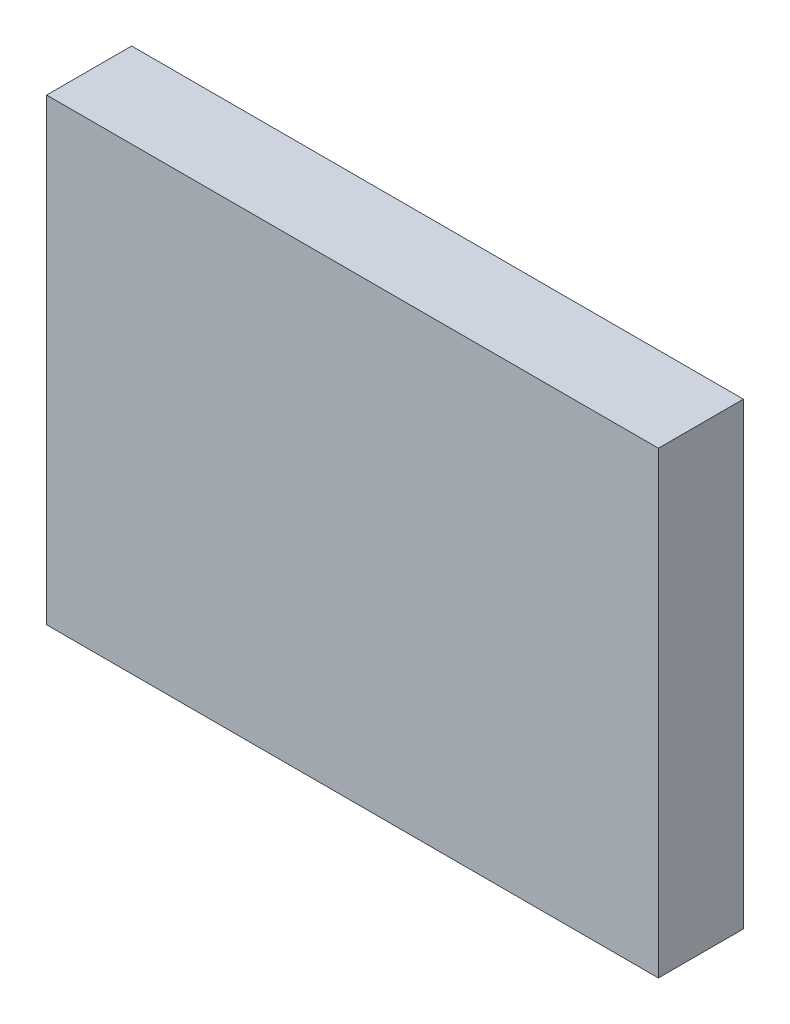
SolidWorks part; units mm, degrees
ref_plane "Спереди" through (0, 0, 0) normal (0, 0, 1) x (1, 0, 0)
ref_plane "Сверху" through (0, 0, 0) normal (0, 1, 0) x (1, 0, 0)
ref_plane "Справа" through (0, 0, 0) normal (1, 0, 0) x (0, 0, -1)
sketch "Эскиз1" plane through (0, 0, 0) normal (0, 0, 1) x (1, 0, 0)
  line L1 (-180, 135) -> (180, 135)
  line L2 (-180, 135) -> (-180, -135)
  line L3 (-180, -135) -> (180, -135)
  line L4 (180, 135) -> (180, -135)
  line L5 (-180, 135) -> (180, -135) construction
  line L6 (-180, -135) -> (180, 135) construction
  point P0 (0, 0)
extrude "Бобышка-Вытянуть1" add sketch "Эскиз1" along normal blind 50
sketch "шлифовка" plane through (0, 0, 50) normal (0, 0, 1) x (1, 0, 0)
  line L1 (-34.1581, 21.8035) -> (-171.6039, 21.8035)
  line L2 (-34.1581, 21.8035) -> (-34.1581, 9.8035)
  line L3 (-34.1581, 9.8035) -> (-171.6039, 9.8035)
  line L4 (-171.6039, 21.8035) -> (-171.6039, 9.8035)
sketch3d "Трехмерный эскиз1"
  point P0 (0, 0, 50.02)
sketch "Перлаж" plane through (0, 0, 50) normal (0, 0, 1) x (1, 0, 0)
  circle A149 centre (-138.9139, -231.1186) radius 1.47
  circle A150 centre (-137.3639, -231.1186) radius 1.47
  circle A151 centre (-135.8139, -231.1186) radius 1.47
  circle A152 centre (-134.2639, -231.1186) radius 1.47
  circle A153 centre (-132.7139, -231.1186) radius 1.47
  circle A154 centre (-131.1639, -231.1186) radius 1.47
  circle A155 centre (-129.6139, -231.1186) radius 1.47
  circle A156 centre (-128.0639, -231.1186) radius 1.47
  circle A157 centre (-126.5139, -231.1186) radius 1.47
  circle A158 centre (-124.9639, -231.1186) radius 1.47
  circle A159 centre (-137.3639, -229.5686) radius 1.47
  circle A160 centre (-135.8139, -229.5686) radius 1.47
  circle A161 centre (-134.2639, -229.5686) radius 1.47
  circle A162 centre (-132.7139, -229.5686) radius 1.47
  circle A163 centre (-131.1639, -229.5686) radius 1.47
  circle A164 centre (-129.6139, -229.5686) radius 1.47
  circle A165 centre (-128.0639, -229.5686) radius 1.47
  circle A166 centre (-126.5139, -229.5686) radius 1.47
  circle A167 centre (-124.9639, -229.5686) radius 1.47
  circle A168 centre (-137.3639, -228.0186) radius 1.47
  circle A169 centre (-135.8139, -228.0186) radius 1.47
  circle A170 centre (-134.2639, -228.0186) radius 1.47
  circle A171 centre (-132.7139, -228.0186) radius 1.47
  circle A172 centre (-131.1639, -228.0186) radius 1.47
  circle A173 centre (-129.6139, -228.0186) radius 1.47
  circle A174 centre (-128.0639, -228.0186) radius 1.47
  circle A175 centre (-126.5139, -228.0186) radius 1.47
  circle A176 centre (-124.9639, -228.0186) radius 1.47
  circle A177 centre (-137.3639, -226.4686) radius 1.47
  circle A178 centre (-135.8139, -226.4686) radius 1.47
  circle A179 centre (-134.2639, -226.4686) radius 1.47
  circle A180 centre (-132.7139, -226.4686) radius 1.47
  circle A181 centre (-131.1639, -226.4686) radius 1.47
  circle A182 centre (-129.6139, -226.4686) radius 1.47
  circle A183 centre (-128.0639, -226.4686) radius 1.47
  circle A184 centre (-126.5139, -226.4686) radius 1.47
  circle A185 centre (-124.9639, -226.4686) radius 1.47
  circle A186 centre (-137.3639, -224.9186) radius 1.47
  circle A187 centre (-135.8139, -224.9186) radius 1.47
  circle A188 centre (-134.2639, -224.9186) radius 1.47
  circle A189 centre (-132.7139, -224.9186) radius 1.47
  circle A190 centre (-131.1639, -224.9186) radius 1.47
  circle A191 centre (-129.6139, -224.9186) radius 1.47
  circle A192 centre (-128.0639, -224.9186) radius 1.47
  circle A193 centre (-126.5139, -224.9186) radius 1.47
  circle A194 centre (-124.9639, -224.9186) radius 1.47
  circle A195 centre (-137.3639, -223.3686) radius 1.47
  circle A196 centre (-135.8139, -223.3686) radius 1.47
  circle A197 centre (-134.2639, -223.3686) radius 1.47
  circle A198 centre (-132.7139, -223.3686) radius 1.47
  circle A199 centre (-131.1639, -223.3686) radius 1.47
  circle A200 centre (-129.6139, -223.3686) radius 1.47
  circle A201 centre (-128.0639, -223.3686) radius 1.47
  circle A202 centre (-126.5139, -223.3686) radius 1.47
  circle A203 centre (-124.9639, -223.3686) radius 1.47
  circle A204 centre (-137.3639, -221.8186) radius 1.47
  circle A205 centre (-135.8139, -221.8186) radius 1.47
  circle A206 centre (-134.2639, -221.8186) radius 1.47
  circle A207 centre (-132.7139, -221.8186) radius 1.47
  circle A208 centre (-131.1639, -221.8186) radius 1.47
  circle A209 centre (-129.6139, -221.8186) radius 1.47
  circle A210 centre (-128.0639, -221.8186) radius 1.47
  circle A211 centre (-126.5139, -221.8186) radius 1.47
  circle A212 centre (-124.9639, -221.8186) radius 1.47
  circle A213 centre (-137.3639, -220.2686) radius 1.47
  circle A214 centre (-135.8139, -220.2686) radius 1.47
  circle A215 centre (-134.2639, -220.2686) radius 1.47
  circle A216 centre (-132.7139, -220.2686) radius 1.47
  circle A217 centre (-131.1639, -220.2686) radius 1.47
  circle A218 centre (-129.6139, -220.2686) radius 1.47
  circle A219 centre (-128.0639, -220.2686) radius 1.47
  circle A220 centre (-126.5139, -220.2686) radius 1.47
  circle A221 centre (-124.9639, -220.2686) radius 1.47
  circle A222 centre (-137.3639, -218.7186) radius 1.47
  circle A223 centre (-135.8139, -218.7186) radius 1.47
  circle A224 centre (-134.2639, -218.7186) radius 1.47
  circle A225 centre (-132.7139, -218.7186) radius 1.47
  circle A226 centre (-131.1639, -218.7186) radius 1.47
  circle A227 centre (-129.6139, -218.7186) radius 1.47
  circle A228 centre (-128.0639, -218.7186) radius 1.47
  circle A229 centre (-126.5139, -218.7186) radius 1.47
  circle A230 centre (-124.9639, -218.7186) radius 1.47
  circle A231 centre (-137.3639, -217.1686) radius 1.47
  circle A232 centre (-135.8139, -217.1686) radius 1.47
  circle A233 centre (-134.2639, -217.1686) radius 1.47
  circle A234 centre (-132.7139, -217.1686) radius 1.47
  circle A235 centre (-131.1639, -217.1686) radius 1.47
  circle A236 centre (-129.6139, -217.1686) radius 1.47
  circle A237 centre (-128.0639, -217.1686) radius 1.47
  circle A238 centre (-126.5139, -217.1686) radius 1.47
  circle A239 centre (-124.9639, -217.1686) radius 1.47
  circle A240 centre (-138.9139, -229.5686) radius 1.47
  circle A241 centre (-138.9139, -228.0186) radius 1.47
  circle A242 centre (-138.9139, -226.4686) radius 1.47
  circle A243 centre (-138.9139, -224.9186) radius 1.47
  circle A244 centre (-138.9139, -223.3686) radius 1.47
  circle A245 centre (-138.9139, -221.8186) radius 1.47
  circle A246 centre (-138.9139, -220.2686) radius 1.47
  circle A247 centre (-138.9139, -218.7186) radius 1.47
  circle A248 centre (-138.9139, -217.1686) radius 1.47
  dimension "D1" = 10
  dimension "D3" = 2.94
  dimension "D2" = 10
